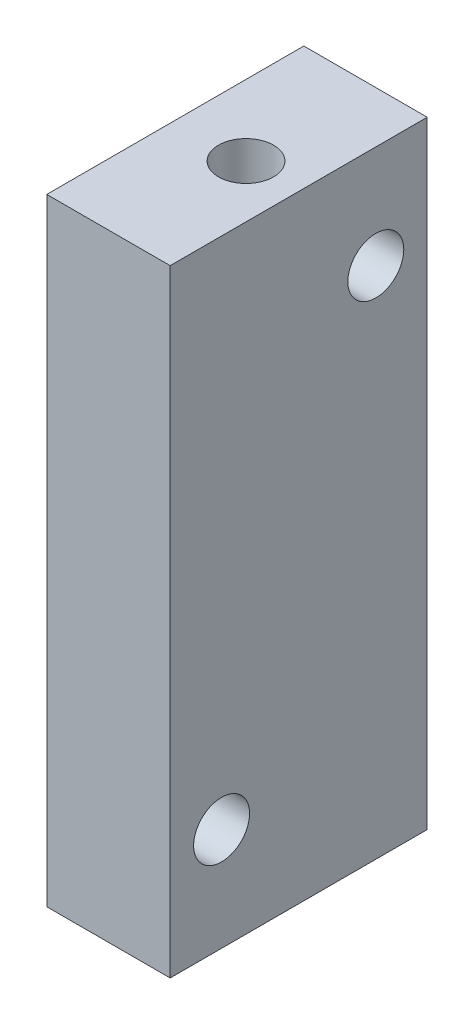
SolidWorks part; units mm, degrees
material "PET"
ref_plane "Front Plane" through (0, 0, 0) normal (1, 0, 0) x (0, 1, 0)
ref_plane "Top Plane" through (0, 0, 0) normal (0, 0, 1) x (0, 1, 0)
ref_plane "Right Plane" through (0, 0, 0) normal (0, 1, 0) x (-1, 0, 0)
sketch "Sketch1" plane through (0, 0, 0) normal (1, 0, 0) x (0, 1, 0)
  line L1 (19.05, -7.9375) -> (-19.05, -7.9375)
  line L2 (19.05, -7.9375) -> (19.05, 7.9375)
  line L3 (19.05, 7.9375) -> (-19.05, 7.9375)
  line L4 (-19.05, -7.9375) -> (-19.05, 7.9375)
  line L5 (19.05, -7.9375) -> (-19.05, 7.9375) construction
  line L6 (19.05, 7.9375) -> (-19.05, -7.9375) construction
  point P0 (0, 0)
  dimension "D1" = 15.875
  dimension "D2" = 38.1
extrude "Boss-Extrude1" add sketch "Sketch1" along normal blind 7.62
sketch "Sketch3" plane through (0, -19.05, 0) normal (0, -1, 0) x (1, 0, 0)
  line L1 (8.7325, -7.9375) -> (0, -7.9375) construction
  line L2 (8.7325, -7.9375) -> (8.7325, 7.9375) construction
  line L3 (8.7325, 7.9375) -> (0, 7.9375) construction
  line L4 (0, -7.9375) -> (0, 7.9375) construction
  line L5 (8.7325, -7.9375) -> (0, 7.9375) construction
  line L6 (8.7325, 7.9375) -> (0, -7.9375) construction
  circle A0 centre (4.3662, 0) radius 1.7
  circle A1 centre (4.3662, 0) radius 5 construction
  point P2 (9.3662, 0)
  point P3 (2.6662, 0)
  point P6 (-19.05, 0)
  dimension "D1" = 3.4
  dimension "D2" = 10
  dimension "D3" = 28.4162
  dimension "D4" = 19.05
extrude "Cut-Extrude1" cut sketch "Sketch3" against normal blind 49.4665 contours A0
sketch "Sketch4" plane through (7.62, 0, 0) normal (1, 0, 0) x (0, 1, 0)
  line L1 (12.7, -4.7625) -> (-12.7, -4.7625) construction
  line L2 (12.7, -4.7625) -> (12.7, 4.7625) construction
  line L3 (12.7, 4.7625) -> (-12.7, 4.7625) construction
  line L4 (-12.7, -4.7625) -> (-12.7, 4.7625) construction
  line L5 (12.7, -4.7625) -> (-12.7, 4.7625) construction
  line L6 (12.7, 4.7625) -> (-12.7, -4.7625) construction
  line L7 (-19.05, 7.9375) -> (-19.05, -7.9375) construction
  line L8 (19.05, 7.9375) -> (-19.05, 7.9375) construction
  circle A0 centre (-12.7, 4.7625) radius 1.7272
  circle A2 centre (12.7, -4.7625) radius 1.7272
  point P0 (0, 0)
  dimension "D3" = 3.4544
  dimension "D1" = 6.35
  dimension "D2" = 3.175
extrude "Cut-Extrude2" cut sketch "Sketch4" against normal blind 22.2885 and the other way blind 3.302
